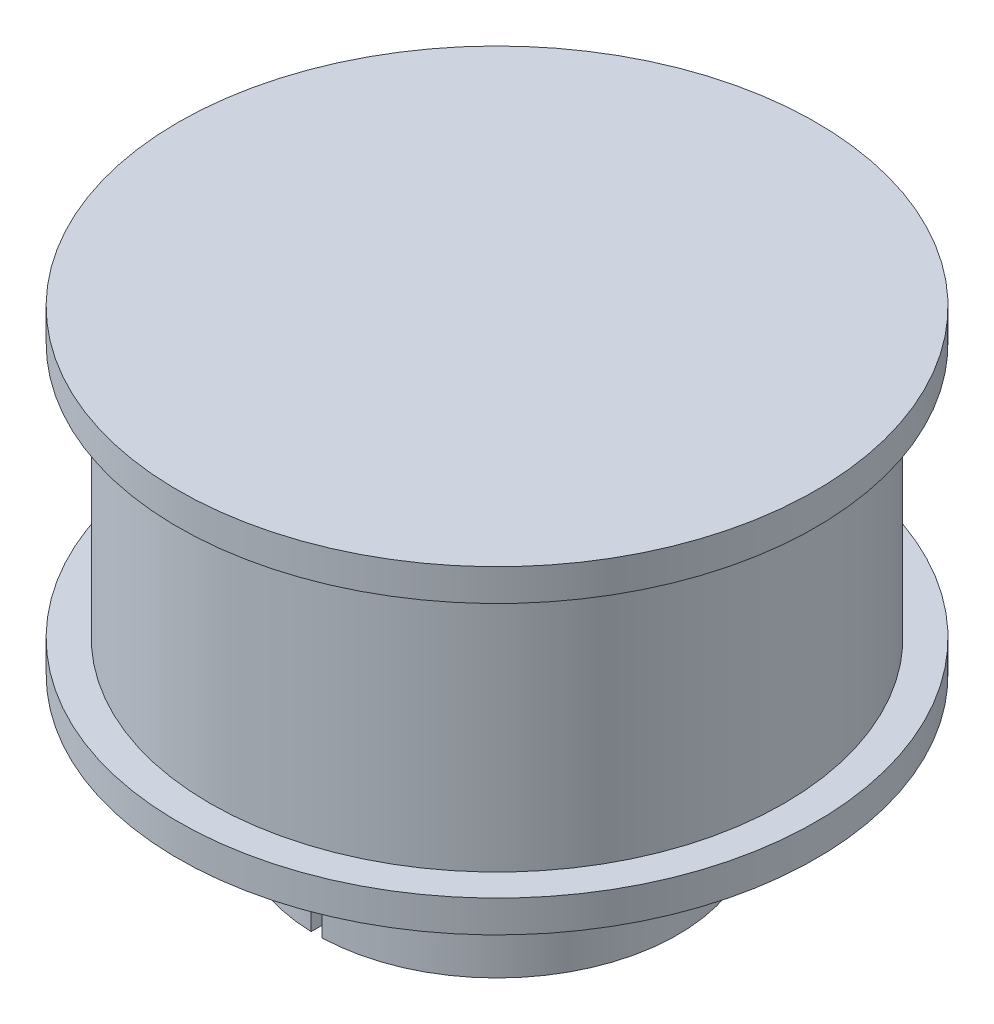
SolidWorks part; units mm, degrees
material "6061 Alloy"
ref_plane "Front Plane" through (0, 0, 0) normal (0, 0, 1) x (1, 0, 0)
ref_plane "Top Plane" through (0, 0, 0) normal (0, 1, 0) x (1, 0, 0)
ref_plane "Right Plane" through (0, 0, 0) normal (1, 0, 0) x (0, 0, -1)
sketch "Sketch1" plane through (0, 0, 0) normal (0, 0, 1) x (1, 0, 0)
  line L2 (-8.5, -6.35) -> (-8.5, 0)
  line L3 (-8.5, 0) -> (-15, 0)
  line L4 (-15, 0) -> (-15, 1.5)
  line L5 (-15, 1.5) -> (-13.5, 1.5)
  line L6 (-13.5, 1.5) -> (-13.5, 13.5)
  line L7 (-13.5, 13.5) -> (-15, 13.5)
  line L8 (-15, 13.5) -> (-15, 15)
  line L9 (-15, 15) -> (0, 15)
  line L10 (0, 15) -> (0, 7.65)
  line L11 (-4, -6.35) -> (-8.5, -6.35)
  line L12 (-4, 7.65) -> (-4, -6.35)
  line L13 (0, 7.65) -> (-4, 7.65)
  dimension "D1" = 8.5
  dimension "D2" = 1.5
  dimension "D3" = 6.35
  dimension "D4" = 1.5
  dimension "D5" = 4
  dimension "D6" = 14
  dimension "D7" = 15
  dimension "D8" = 15
revolve "Revolve1" add sketch "Sketch1" angle 360 about L10
ref_plane "Plane1" through (-8.5, 0, 0) normal (-1, 0, 0) x (0, 0, 1)
hole_wizard "CBORE for M2 SHCS1" positions "Sketch2" profile "Sketch3" counterbore size "M2" standard "ANSI Metric" end condition through all
sketch "Sketch2" plane through (-8.5, 0, 0) normal (1, 0, 0) x (0, 0, -1)
  line L0 (-8.5, -6.35) -> (8.5, -6.35) construction
  point P0 (-6.25, -3.175)
  dimension "D1" = 6.25
  dimension "D2" = 3.175
sketch "Sketch3" plane through (-8.5, -3.175, 6.25) normal (0, 1, 0) x (0, 0, 1)
  line L0 (0, 0) -> (0, 23.5)
  line L1 (0, 23.5) -> (1.2, 23.5)
  line L3 (1.2, 23.5) -> (1.2, 2)
  line L4 (1.2, 2) -> (2.2, 2)
  line L5 (2.2, 2) -> (2.2, 0)
  line L7 (2.2, 0) -> (0, 0)
  line L11 (0, -6.35) -> (0, 107.95) construction
  dimension "Thru Hole Dia." = 2.4
  dimension "Thru Hole Depth" = 23.5
  dimension "C'Bore Dia." = 4.4
  dimension "C'Bore Depth" = 2
sketch "Sketch4" plane through (0, 0, 0) normal (0, 1, 0) x (1, 0, 0)
  line L0 (-0.25, -8.5) -> (-0.25, 0)
  line L1 (-0.25, -8.5) -> (0.25, -8.5)
  line L2 (-0.25, 0) -> (0.25, 0)
  line L3 (0.25, -8.5) -> (0.25, 0)
  line L4 (-0.25, -8.5) -> (0.25, 0) construction
  line L5 (-0.25, 0) -> (0.25, -8.5) construction
  circle A0 centre (0, 0) radius 8.5 construction
  point P1 (0, -4.25)
  dimension "D1" = 0.5
extrude "Cut-Extrude1" cut sketch "Sketch4" against normal up to next
sketch "Sketch5" plane through (0, 0, 0) normal (0, 0, 1) x (1, 0, 0)
  line L0 (-9, -0.5) -> (-9, 0)
  line L1 (-9, -0.5) -> (9, -0.5)
  line L2 (-9, 0) -> (9, 0)
  line L3 (9, -0.5) -> (9, 0)
  line L4 (-9, -0.5) -> (9, 0) construction
  line L5 (-9, 0) -> (9, -0.5) construction
  point P1 (0, -0.25)
  dimension "D1" = 0.5
  dimension "D2" = 18
extrude "Cut-Extrude2" cut sketch "Sketch5" along normal through all
